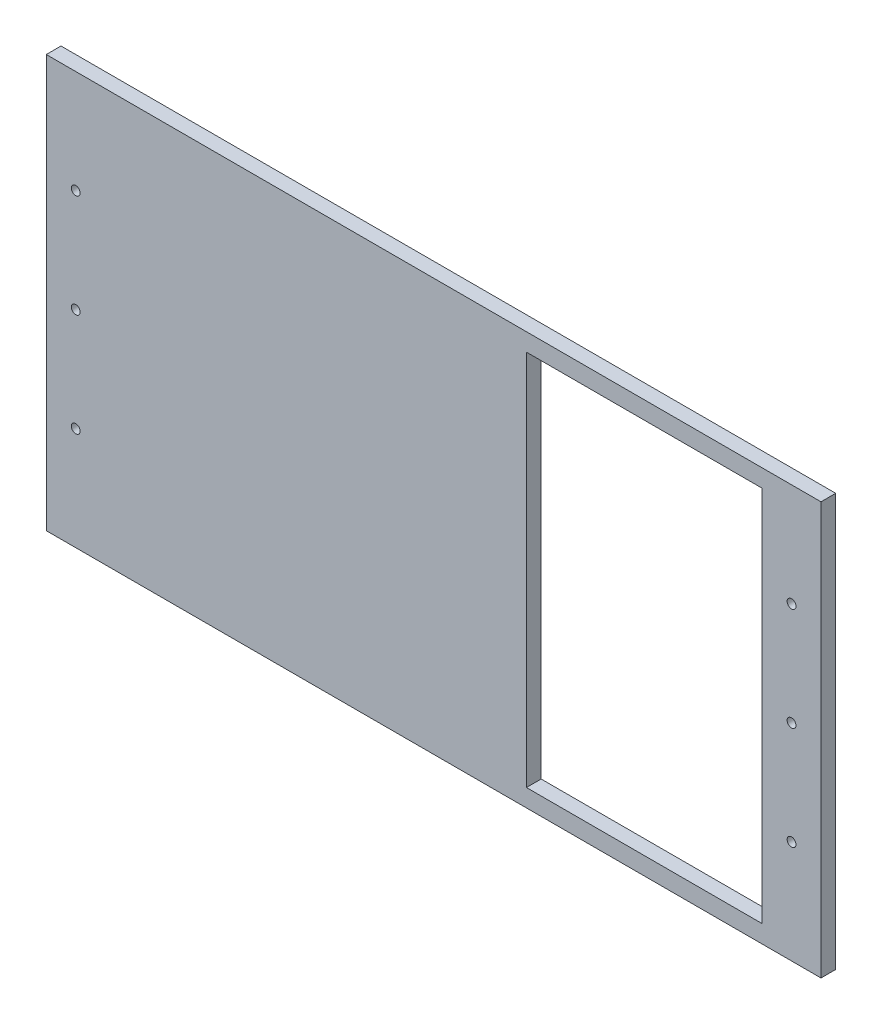
SolidWorks part; units mm, degrees
ref_plane "前视基准面" through (0, 0, 0) normal (0, 0, 1) x (1, 0, 0)
ref_plane "上视基准面" through (0, 0, 0) normal (0, 1, 0) x (1, 0, 0)
ref_plane "右视基准面" through (0, 0, 0) normal (1, 0, 0) x (0, 0, -1)
sketch "草图1" plane through (0, 0, 0) normal (0, 0, 1) x (1, 0, 0)
  line L1 (-131.5, -70) -> (131.5, -70)
  line L2 (-131.5, -70) -> (-131.5, 70)
  line L3 (-131.5, 70) -> (131.5, 70)
  line L4 (131.5, -70) -> (131.5, 70)
  line L5 (-131.5, -70) -> (131.5, 70) construction
  line L6 (-131.5, 70) -> (131.5, -70) construction
  line L10 (31.5, 64) -> (111.5, 64)
  line L14 (31.5, 64) -> (31.5, -64)
  line L15 (31.5, -64) -> (111.5, -64)
  line L16 (111.5, 64) -> (111.5, -64)
  circle A0 centre (-121.5, 35) radius 1.5
  circle A1 centre (-121.5, 0) radius 1.5
  circle A2 centre (-121.5, -35) radius 1.5
  circle A3 centre (121.5, -35) radius 1.5
  circle A4 centre (121.5, 0) radius 1.5
  circle A5 centre (121.5, 35) radius 1.5
  point P0 (0, 0)
  dimension "D7" = 6
  dimension "D1" = 263
  dimension "D2" = 140
  dimension "D3" = 6
  dimension "D8" = 80
  dimension "D9" = 20
extrude "凸台-拉伸1" add sketch "草图1" along normal blind 5
